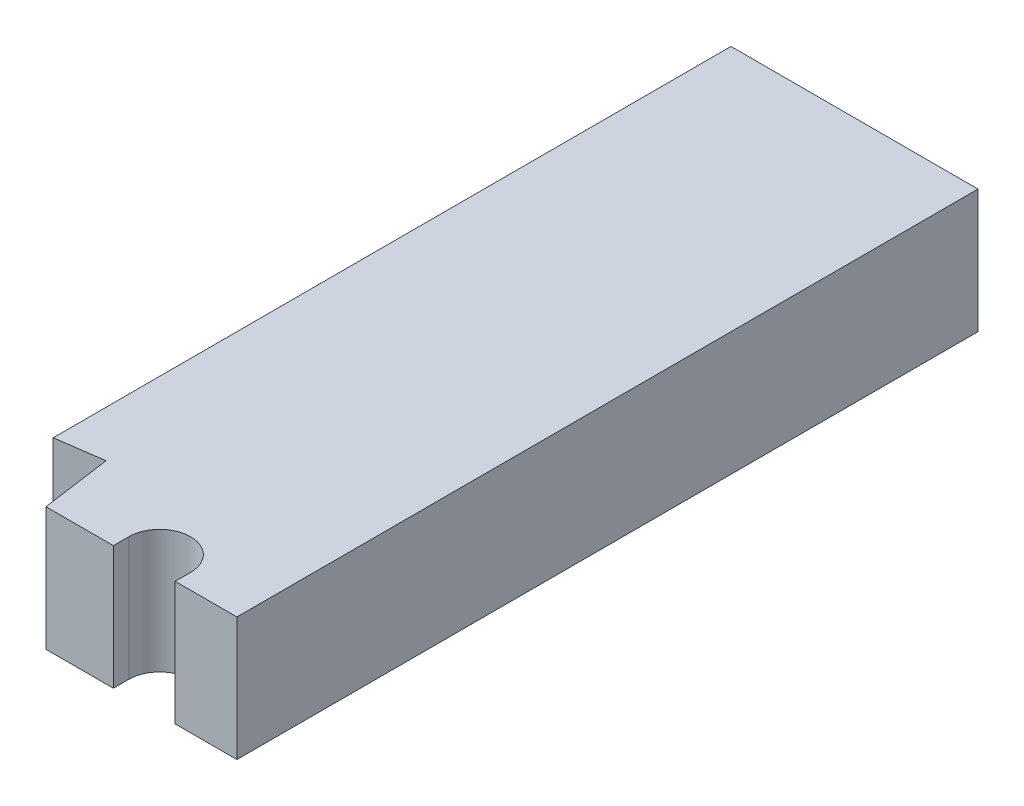
SolidWorks part; units mm, degrees
material "Pine"
ref_plane "X-Y Datum" through (0, 0, 0) normal (0, 0, 1) x (1, 0, 0)
ref_plane "X-Z Datum" through (0, 0, 0) normal (0, 1, 0) x (1, 0, 0)
ref_plane "Y-Z Datum" through (0, 0, 0) normal (1, 0, 0) x (0, 0, -1)
sketch "Sketch1" plane through (0, 0, 0) normal (0, 0, 1) x (1, 0, 0)
  line L1 (-50.8, 25.4) -> (50.8, 25.4)
  line L2 (-50.8, 25.4) -> (-50.8, -25.4)
  line L3 (-50.8, -25.4) -> (50.8, -25.4)
  line L4 (50.8, 25.4) -> (50.8, -25.4)
  line L5 (-50.8, 25.4) -> (50.8, -25.4) construction
  line L6 (-50.8, -25.4) -> (50.8, 25.4) construction
  point P0 (0, 0)
  dimension "D1" = 101.6
  dimension "D2" = 50.8
extrude "Boss-Extrude1" add sketch "Sketch1" along normal blind 304.8
sketch "Sketch2" plane through (0, 25.4, 0) normal (0, 1, 0) x (1, 0, 0)
  line L0 (50.8, -304.8) -> (50.8, 0) construction
  line L1 (-50.8, -278.7499) -> (-31.75, -276.0726)
  line L2 (50.8, -304.8) -> (-50.8, -304.8) construction
  line L3 (25.4, -298.45) -> (25.4, -304.8)
  line L4 (25.4, -304.8) -> (23.6985, -304.8)
  line L5 (0, -298.45) -> (0, -304.8)
  line L6 (0, -304.8) -> (1.7015, -304.8)
  line L7 (-31.75, -276.0726) -> (-27.7126, -304.8)
  line L8 (-50.8, -304.8) -> (-50.8, 0) construction
  line L9 (-50.8, -304.8) -> (50.8, -304.8) construction
  line L10 (-50.8, -278.7499) -> (-50.8, -304.8)
  line L11 (-50.8, -304.8) -> (-27.7126, -304.8)
  circle A0 centre (12.7, -298.45) radius 12.7
  point P2 (0, 0)
  line M2 (-50.8, 0) -> (-50.8, -304.8)
  line M3 (-50.8, -304.8) -> (50.8, -304.8)
  dimension "D2" = 25.4
  dimension "D1" = 38.1
  dimension "D3" = 6.35
  dimension "D4" = 8
  dimension "D5" = 28.7274
  dimension "D6" = 19.05
extrude "Cut-Extrude1" cut sketch "Sketch2" against normal through all both and the other way through all contours A0 M3 | A0 L3 M3 | A0 L5 M3 | L7 L1 M2 M3
